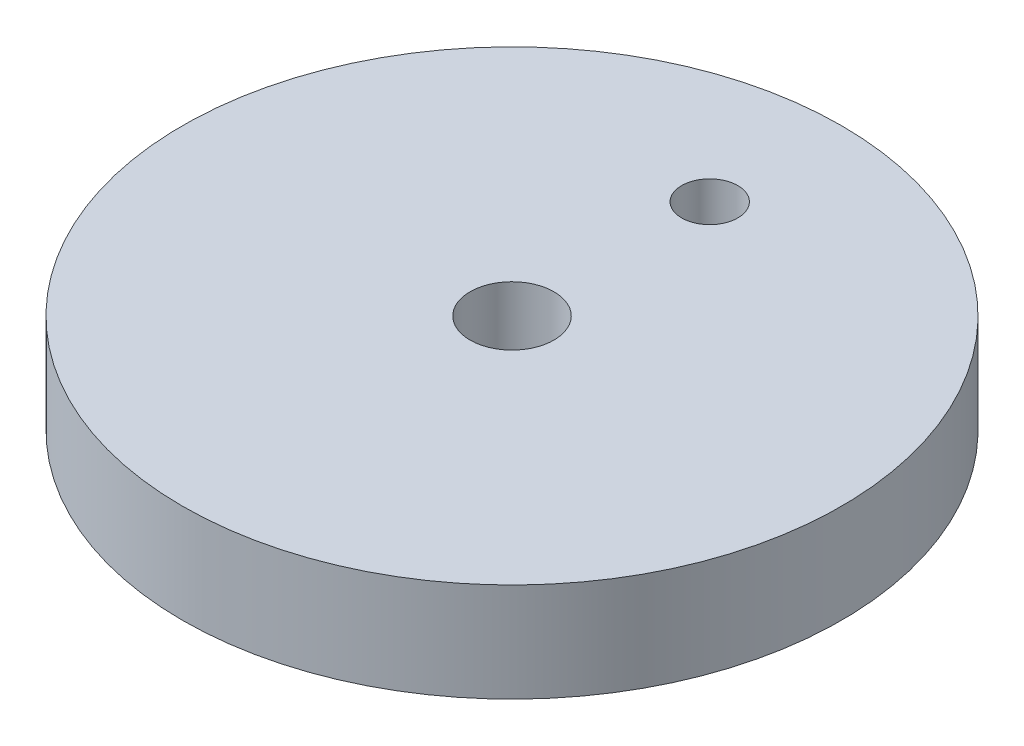
SolidWorks part; units mm, degrees
ref_plane "Front Plane" through (0, 0, 0) normal (0, 0, 1) x (1, 0, 0)
ref_plane "Top Plane" through (0, 0, 0) normal (0, 1, 0) x (1, 0, 0)
ref_plane "Right Plane" through (0, 0, 0) normal (1, 0, 0) x (0, 0, -1)
sketch "Sketch1" plane through (0, 0, 0) normal (0, 1, 0) x (1, 0, 0)
  circle A0 centre (0, 0) radius 15.875
  dimension "D1" = 31.75
extrude "Boss-Extrude1" add sketch "Sketch1" along normal blind 4.7625
hole_wizard "#10-32 Tapped Hole1" positions "Sketch3" profile "Sketch4" tap size "#10-32" standard "ANSI Inch" end condition up to next
sketch "Sketch3" plane through (0, 4.7625, 0) normal (0, 1, 0) x (1, 0, 0)
  point P0 (0, 0)
sketch "Sketch4" plane through (0, 4.7625, 0) normal (1, 0, 0) x (0, 0, 1)
  line L0 (0, 0) -> (0, 4.7625)
  line L1 (0, 4.7625) -> (2.0193, 4.7625)
  line L2 (2.0193, 4.7625) -> (2.0193, 0)
  line L5 (2.0193, 0) -> (0, 0)
  line L11 (0, -6.35) -> (0, 107.95) construction
  dimension "Thru Tap Drill Dia." = 4.0386
  dimension "Thru Tap Drill Depth" = 4.7625
cosmetic thread "Hole Thread1" parameters "D2"=4.826
hole_wizard "#6-32 Tapped Hole1" positions "Sketch6" profile "Sketch5" tap size "#6-32" standard "ANSI Inch" end condition up to next
sketch "Sketch6" plane through (0, 4.7625, 0) normal (0, 1, 0) x (1, 0, 0)
  circle A0 centre (0, 0) radius 2.0193 construction
  point P0 (0, 9.525)
  dimension "D1" = 9.525
sketch "Sketch5" plane through (0, 4.7625, -9.525) normal (1, 0, 0) x (0, 0, 1)
  line L0 (0, 0) -> (0, 4.7625)
  line L1 (0, 4.7625) -> (1.3525, 4.7625)
  line L2 (1.3525, 4.7625) -> (1.3525, 0)
  line L5 (1.3525, 0) -> (0, 0)
  line L11 (0, -6.35) -> (0, 107.95) construction
  dimension "Thru Tap Drill Dia." = 2.7051
  dimension "Thru Tap Drill Depth" = 4.7625
cosmetic thread "Hole Thread2" parameters "D2"=3.5052
